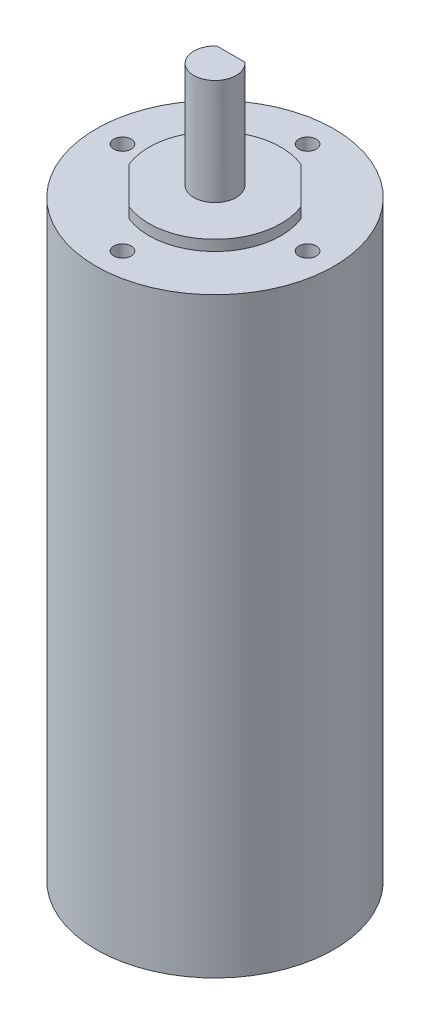
SolidWorks part; units mm, degrees
material "AISI 1020"
ref_plane "Front Plane" through (0, 0, 0) normal (0, 0, 1) x (1, 0, 0)
ref_plane "Top Plane" through (0, 0, 0) normal (0, 1, 0) x (1, 0, 0)
ref_plane "Right Plane" through (0, 0, 0) normal (1, 0, 0) x (0, 0, -1)
sketch "Sketch1" plane through (0, 0, 0) normal (0, 1, 0) x (1, 0, 0)
  circle A0 centre (0, 0) radius 22.5
  dimension "D1" = 45
extrude "Boss-Extrude1" add sketch "Sketch1" along normal blind 111.9
sketch "Sketch2" plane through (0, 111.9, 0) normal (0, 1, 0) x (1, 0, 0)
  line L0 (-11.5958, -4.6676) -> (-4.6676, -11.5958)
  line L1 (11.5958, 4.6676) -> (4.6676, 11.5958)
  line L2 (-17.5004, 0) -> (24.7615, 0) construction
  arc A0 (-4.6676, -11.5958) -> (11.5958, 4.6676) centre (0, 0) ccw
  arc A1 (4.6676, 11.5958) -> (-11.5958, -4.6676) centre (0, 0) ccw
  dimension "D1" = 25
  dimension "D2" = 23
  dimension "D3" = 45
  dimension "D4" = 11.5
extrude "Boss-Extrude2" add sketch "Sketch2" along normal blind 2
sketch "Sketch3" plane through (0, 113.9, 0) normal (0, 1, 0) x (1, 0, 0)
  circle A0 centre (0, 0) radius 4
  dimension "D1" = 8
extrude "Boss-Extrude3" add sketch "Sketch3" along normal blind 8
sketch "Sketch4" plane through (0, 121.9, 0) normal (0, 1, 0) x (1, 0, 0)
  line L0 (-2.6458, 3) -> (2.6458, 3)
  arc A0 (-2.6458, 3) -> (2.6458, 3) centre (0, 0) ccw
  dimension "D2" = 8
  dimension "D1" = 3
extrude "Boss-Extrude4" add sketch "Sketch4" along normal blind 12
sketch "Sketch5" plane through (0, 111.9, 0) normal (0, 1, 0) x (1, 0, 0)
  line L0 (-29.0728, 0) -> (28.7891, 0) construction
  line L1 (0, 31.9561) -> (0, -35.387) construction
  circle A0 centre (-17.5, 0) radius 1.65
  circle A1 centre (0, 17.5) radius 1.65
  circle A2 centre (17.5, 0) radius 1.65
  circle A3 centre (0, -17.5) radius 1.65
  point P16 (0, 0)
  dimension "D1" = 3.3
  dimension "D3" = 17.5
  dimension "D4" = 17.5
  dimension "D5" = 17.5
  dimension "D2" = 4
extrude "Cut-Extrude1" cut sketch "Sketch5" against normal blind 6
